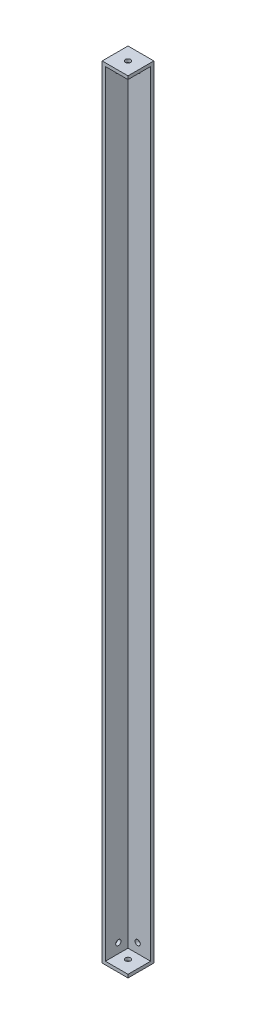
SolidWorks part; units mm, degrees
ref_plane "前视基准面" through (0, 0, 0) normal (0, 0, 1) x (1, 0, 0)
ref_plane "上视基准面" through (0, 0, 0) normal (0, 1, 0) x (1, 0, 0)
ref_plane "右视基准面" through (0, 0, 0) normal (1, 0, 0) x (0, 0, -1)
sketch "草图1" plane through (0, 0, 0) normal (0, 1, 0) x (1, 0, 0)
  line L0 (0, 44.2289) -> (0, -40.8267) construction
  line L1 (-20, 20) -> (20, 20)
  line L2 (-55.995, 0) -> (50.6081, 0) construction
  line L3 (20, 20) -> (20, -20)
  line L4 (20, -20) -> (-20, -20)
  line L5 (-20, -20) -> (-20, 20)
extrude "凸台-拉伸1" add sketch "草图1" along normal blind 5
sketch "草图2" plane through (0, 5, 0) normal (0, 1, 0) x (1, 0, 0)
  circle A0 centre (0, 0) radius 4.05
extrude "切除-拉伸1" cut sketch "草图2" against normal blind 5
sketch "草图3" plane through (0, 5, 0) normal (0, 1, 0) x (1, 0, 0)
  line L0 (-20, 20) -> (-20, -20)
  line L1 (-20, -20) -> (-15, -20)
  line L2 (-20, -20) -> (20, -20) construction
  line L3 (-15, -20) -> (-15, 15)
  line L4 (-15, 15) -> (20, 15)
  line L5 (20, -20) -> (20, 20) construction
  line L6 (20, 15) -> (20, 20)
  line L7 (20, 20) -> (-20, 20)
extrude "凸台-拉伸2" add sketch "草图3" along normal blind 600
mirror "镜向1" about plane through (0, 605, 0) normal (0, 1, 0) of "凸台-拉伸2", "切除-拉伸1", "凸台-拉伸1"
sketch "草图4" plane through (0, 1205, 0) normal (0, 1, 0) x (1, 0, 0)
  line L1 (-20, 20) -> (20, 20)
  line L2 (-20, 20) -> (-20, -20)
  line L3 (-20, -20) -> (20, -20)
  line L4 (20, 20) -> (20, -20)
  circle A0 centre (0, 0) radius 4.05
extrude "凸台-拉伸3" add sketch "草图4" along normal blind 5
sketch "草图5" plane through (0, 0, -15) normal (0, 0, 1) x (1, 0, 0)
  line L0 (-20, 0) -> (20, 0) construction
  circle A0 centre (0, 20) radius 4.05
  dimension "D1" = 20
extrude "切除-拉伸2" cut sketch "草图5" against normal blind 5
ref_plane "基准面1" through (0, 605, 0) normal (0, -1, 0) x (-1, 0, 0)
mirror "镜向2" about plane through (0, 605, 0) normal (0, -1, 0) of "切除-拉伸2"
sketch "草图6" plane through (-15, 0, 0) normal (1, 0, 0) x (0, 0, -1)
  line L0 (-20, 0) -> (20, 0) construction
  circle A0 centre (0, 20) radius 4.05
  dimension "D1" = 20
extrude "切除-拉伸3" cut sketch "草图6" against normal blind 5
mirror "镜向3" about plane through (0, 605, 0) normal (0, -1, 0) of "切除-拉伸3"
